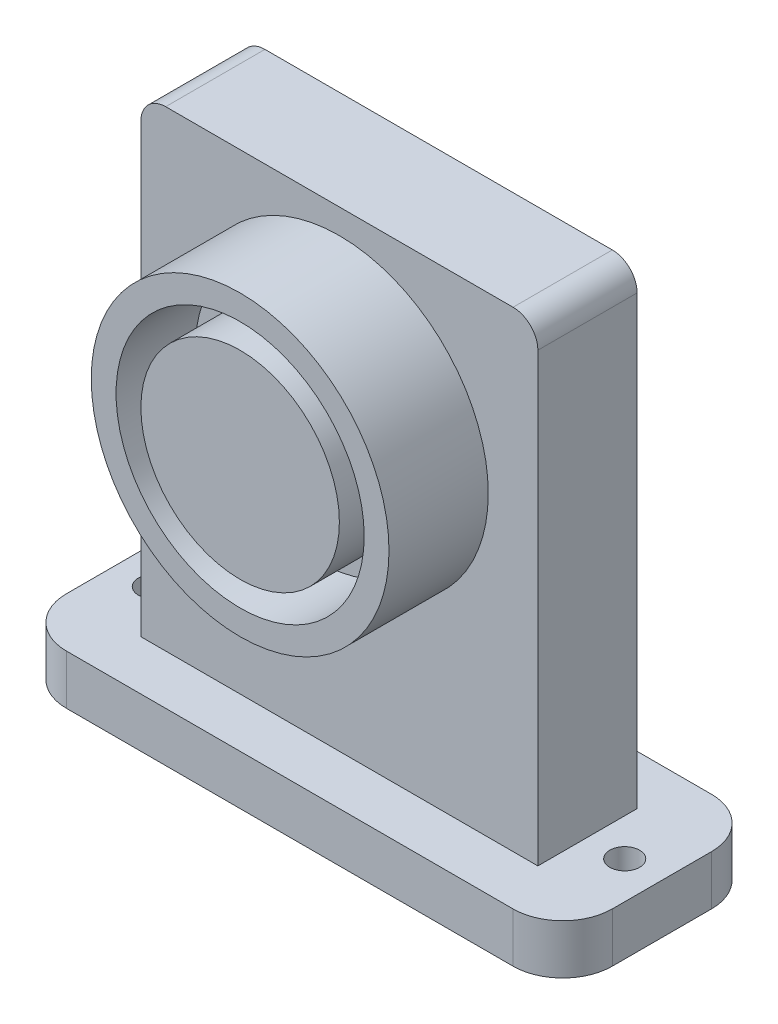
SolidWorks part; units mm, degrees
ref_plane "Front Plane" through (0, 0, 0) normal (0, 0, 1) x (1, 0, 0)
ref_plane "Top Plane" through (0, 0, 0) normal (0, 1, 0) x (1, 0, 0)
ref_plane "Right Plane" through (0, 0, 0) normal (1, 0, 0) x (0, 0, -1)
sketch "Sketch1" plane through (0, 0, 0) normal (0, 0, 1) x (1, 0, 0)
  line L5 (-20, 35) -> (20, -35) construction
  line L6 (-20, -35) -> (20, 35) construction
  line L14 (-20, 35) -> (20, 35)
  line L15 (-20, 35) -> (-20, -35)
  line L16 (-20, -35) -> (20, -35)
  line L17 (20, 35) -> (20, -35)
  point P0 (0, 0)
  dimension "D1" = 70
  dimension "D2" = 40
extrude "Boss-Extrude1" add sketch "Sketch1" along normal blind 10
sketch "Sketch4" plane through (0, 0, 10) normal (0, 0, 1) x (1, 0, 0)
  circle A0 centre (0, 0) radius 15
  dimension "D1" = 30
extrude "Boss-Extrude3" add sketch "Sketch4" along normal blind 10
sketch "Sketch5" plane through (0, 0, 20) normal (0, 0, 1) x (1, 0, 0)
  circle A0 centre (0, 0) radius 12.5
  circle A1 centre (0, 0) radius 10
  dimension "D1" = 25
extrude "Cut-Extrude2" cut sketch "Sketch5" against normal blind 8
sketch "Sketch6" plane through (0, 35, 0) normal (0, 1, 0) x (1, 0, 0)
  line L1 (-20, 0) -> (20, 0)
  line L2 (-20, 0) -> (-20, -10)
  line L3 (-20, -10) -> (20, -10)
  line L4 (20, 0) -> (20, -10)
extrude "Cut-Extrude3" cut sketch "Sketch6" against normal blind 17.5
fillet "Fillet4" radius 2.5 2 edges at (20, 17.5, 5) (-20, 17.5, 5)
sketch "Sketch11" plane through (0, -35, 0) normal (0, -1, 0) x (1, 0, 0)
  line L0 (0, 10) -> (0, 0) construction
  line L1 (-20, 10) -> (20, 10) construction
  line L2 (-27.5, 5) -> (-20, 5) construction
  line L3 (-22.5, 15) -> (22.5, 15)
  line L4 (-27.5, 10) -> (-27.5, 0)
  line L5 (-22.5, -5) -> (22.5, -5)
  line L6 (27.5, 10) -> (27.5, 0)
  line L7 (-27.5, 15) -> (27.5, -5) construction
  line L8 (-27.5, -5) -> (27.5, 15) construction
  line L9 (-20, 10) -> (-20, 0) construction
  line L11 (-20, 10) -> (20, 10)
  line L12 (-20, 10) -> (-20, 0)
  line L13 (-20, 0) -> (20, 0)
  line L14 (20, 10) -> (20, 0)
  line L15 (-20, 10) -> (20, 0) construction
  line L16 (-20, 0) -> (20, 10) construction
  arc A0 (22.5, 15) -> (27.5, 10) centre (22.5, 10) cw
  arc A1 (22.5, -5) -> (27.5, 0) centre (22.5, 0) ccw
  arc A2 (-27.5, 0) -> (-22.5, -5) centre (-22.5, 0) ccw
  arc A3 (-22.5, 15) -> (-27.5, 10) centre (-22.5, 10) ccw
  circle A4 centre (-23.75, 5) radius 1.5
  circle A5 centre (23.75, 5) radius 1.5
  point P5 (0, 5)
  point P30 (0, 5)
  dimension "D3" = 5
  dimension "D4" = 3
  dimension "D1" = 20
  dimension "D2" = 55
extrude "Boss-Extrude4" add sketch "Sketch11" against normal blind 5
